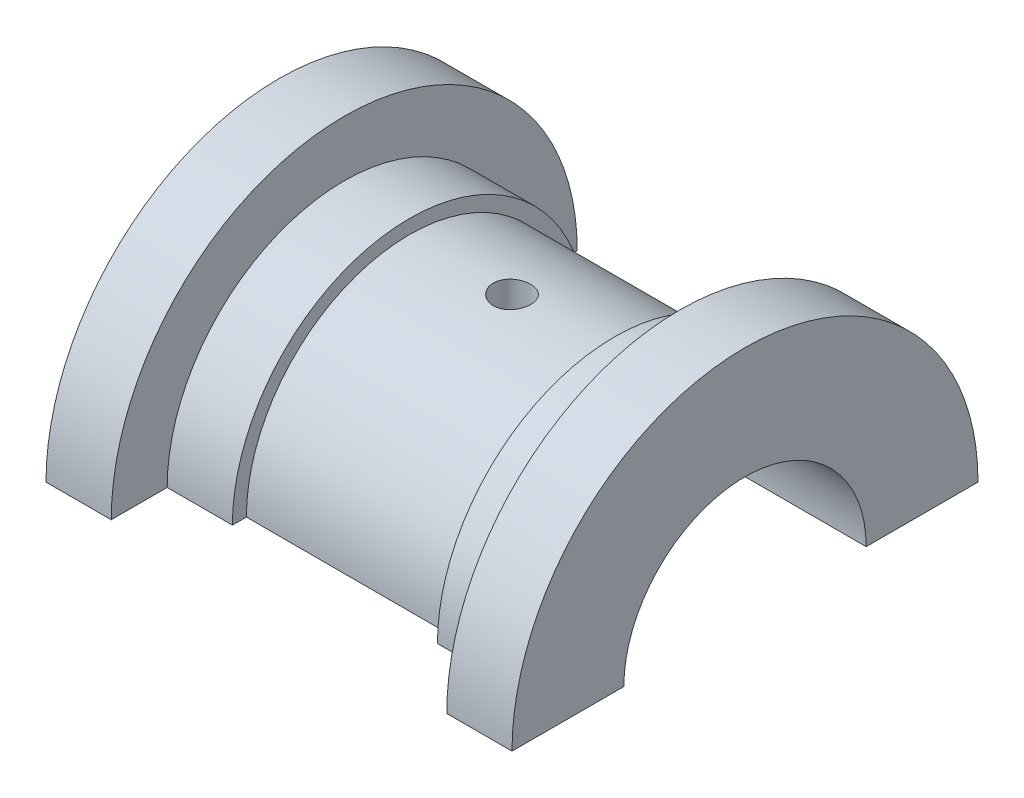
SolidWorks part; units mm, degrees
ref_plane "Front Plane" through (0, 0, 0) normal (0, 0, 1) x (1, 0, 0)
ref_plane "Top Plane" through (0, 0, 0) normal (0, 1, 0) x (1, 0, 0)
ref_plane "Right Plane" through (0, 0, 0) normal (1, 0, 0) x (0, 0, -1)
sketch "Sketch1" plane through (0, 0, 0) normal (1, 0, 0) x (0, 0, -1)
  line L0 (-25, 0) -> (-13, 0)
  line L1 (13, 0) -> (25, 0)
  arc A0 (25, 0) -> (-25, 0) centre (0, 0) ccw
  arc A1 (13, 0) -> (-13, 0) centre (0, 0) ccw
extrude "Boss-Extrude4" add sketch "Sketch1" along normal blind 50
ref_plane "Plane1" through (7, 0, 0) normal (-1, 0, 0) x (0, 0, 1)
sketch "Sketch4" plane through (7, 0, 0) normal (-1, 0, 0) x (0, 0, 1)
  line L0 (-19, 0) -> (19, 0)
  line L1 (-19, 0) -> (-17.5, 0)
  line L2 (17.5, 0) -> (19, 0)
  line L3 (17.5, 0) -> (19, 0)
  line L4 (-19, 0) -> (-17.5, 0)
  arc A0 (17.5, 0) -> (-17.5, 0) centre (0, 0) ccw
  arc A1 (19, 0) -> (-19, 0) centre (0, 0) ccw
extrude "Cut-Extrude-Thin1" cut sketch "Sketch4" against normal blind 50 thin contours A0 | A1
sketch "Sketch5" plane through (7, 0, 0) normal (1, 0, 0) x (0, 0, -1)
  line L0 (-19, 0) -> (-17.5, 0)
  line L1 (17.5, 0) -> (19, 0)
  arc A0 (19, 0) -> (-19, 0) centre (0, 0) ccw
  arc A1 (17.5, 0) -> (-17.5, 0) centre (0, 0) ccw
extrude "Boss-Extrude6" add sketch "Sketch5" along normal blind 7
sketch "Sketch8" plane through (50, 0, 0) normal (1, 0, 0) x (0, 0, -1)
  line L0 (-25, 0) -> (-17.5, 0)
  line L1 (17.5, 0) -> (25, 0)
  arc A0 (25, 0) -> (-25, 0) centre (0, 0) ccw
  arc A1 (17.5, 0) -> (-17.5, 0) centre (0, 0) ccw
extrude "Boss-Extrude8" add sketch "Sketch8" against normal blind 7
sketch "Sketch9" plane through (43, 0, 0) normal (-1, 0, 0) x (0, 0, 1)
  line L0 (-19, 0) -> (-17.5, 0)
  line L1 (17.5, 0) -> (19, 0)
  arc A0 (19, 0) -> (-19, 0) centre (0, 0) ccw
  arc A1 (17.5, 0) -> (-17.5, 0) centre (0, 0) ccw
extrude "Boss-Extrude9" add sketch "Sketch9" along normal blind 7
ref_plane "Plane2" through (0, 17.5, 0) normal (0, 1, 0) x (1, 0, 0)
sketch "Sketch10" plane through (0, 17.5, 0) normal (0, 1, 0) x (1, 0, 0)
  circle A0 centre (25, 0) radius 2
extrude "Cut-Extrude1" cut sketch "Sketch10" against normal through all
